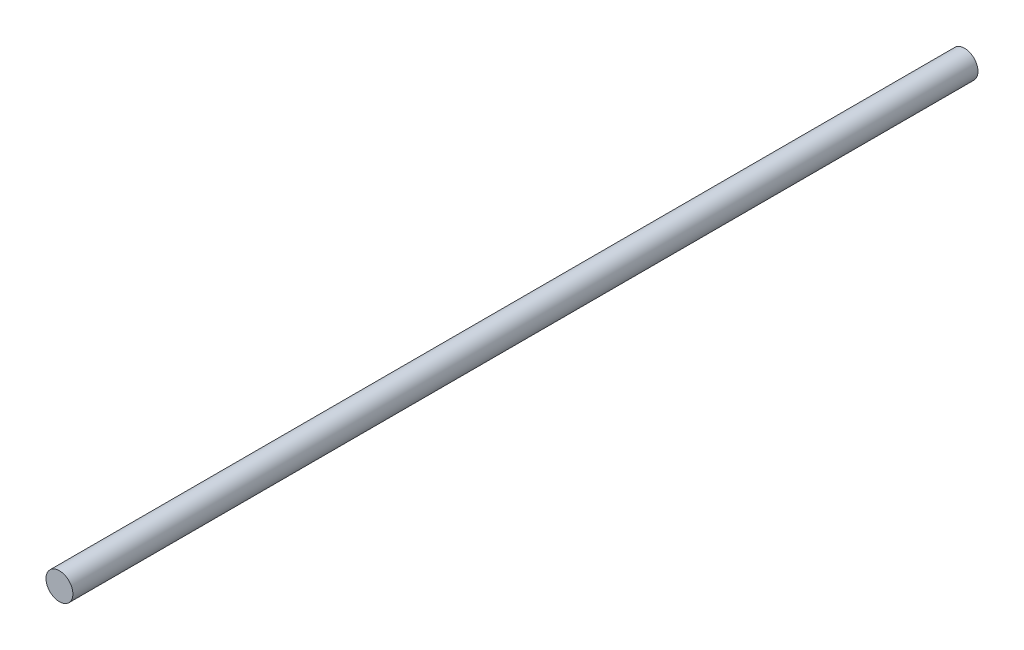
SolidWorks part; units mm, degrees
ref_plane "Front Plane" through (0, 0, 0) normal (0, 0, 1) x (1, 0, 0)
ref_plane "Top Plane" through (0, 0, 0) normal (0, 1, 0) x (1, 0, 0)
ref_plane "Right Plane" through (0, 0, 0) normal (1, 0, 0) x (0, 0, -1)
sketch "Sketch1" plane through (0, 0, 0) normal (0, 0, 1) x (1, 0, 0)
  circle A0 centre (0, 0) radius 8.025
  dimension "D1" = 16.05
extrude "Boss-Extrude1" add sketch "Sketch1" along normal mid plane 540
sketch "Sketch2" plane through (0, 0, 270) normal (0, 0, 1) x (1, 0, 0)
  circle A0 centre (0, 0) radius 8.025 construction
  circle A1 centre (0, 0) radius 8.025
curve "Helix/Spiral2" pitch 5 height 500 turns 100
